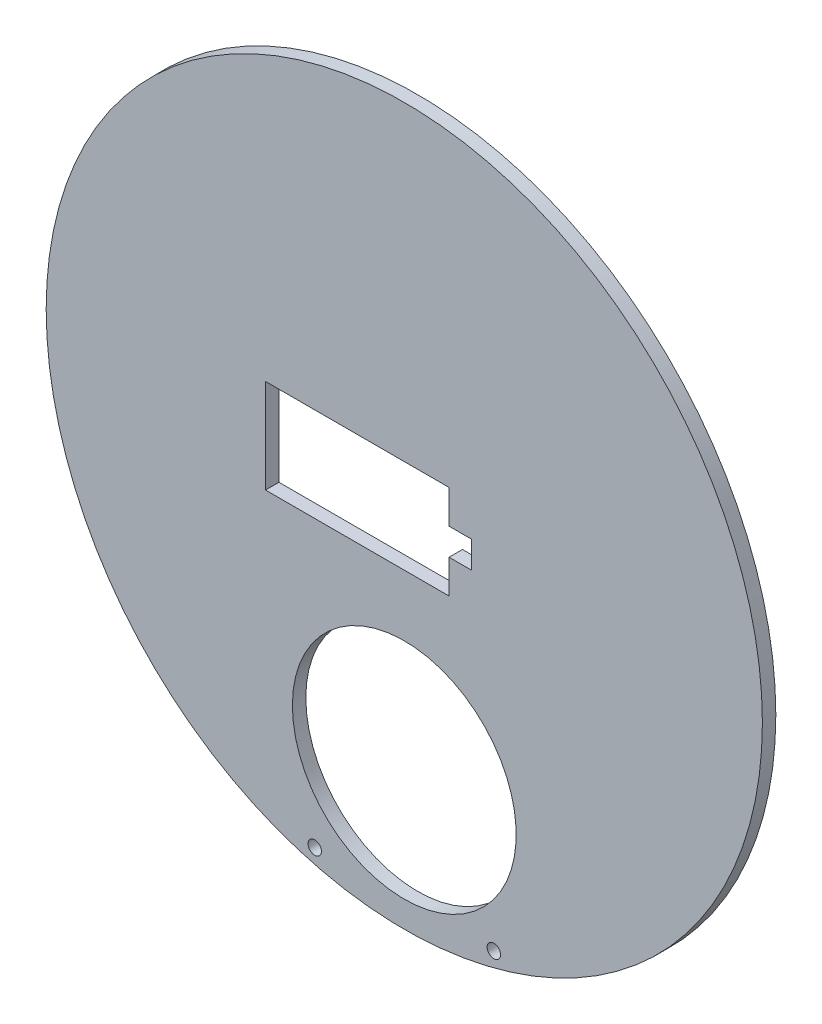
SolidWorks part; units mm, degrees
ref_plane "Plan de face" through (0, 0, 0) normal (0, 0, 1) x (1, 0, 0)
ref_plane "Plan de dessus" through (0, 0, 0) normal (0, 1, 0) x (1, 0, 0)
ref_plane "Plan de droite" through (0, 0, 0) normal (1, 0, 0) x (0, 0, -1)
sketch "Esquisse1" plane through (0, 0, 0) normal (0, 0, 1) x (1, 0, 0)
  circle A0 centre (-11.1979, 8.2445) radius 80
  dimension "D1" = 160
extrude "Boss.-Extru.1" add sketch "Esquisse1" along normal blind 3
sketch "Esquisse2" plane through (0, 0, 0) normal (0, 0, -1) x (-1, 0, 0)
  line L0 (11.1979, 88.2445) -> (11.1979, -71.7555) construction
  line L1 (91.1979, 8.2445) -> (-68.8021, 8.2445) construction
  line L2 (1.1979, 5.2445) -> (1.1979, -2.2555)
  line L3 (1.1979, 18.7445) -> (42.1979, 18.7445)
  line L4 (1.1979, 18.7445) -> (1.1979, 11.2445)
  line L5 (1.1979, -2.2555) -> (42.1979, -2.2555)
  line L6 (42.1979, 18.7445) -> (42.1979, -2.2555)
  line L7 (-3.8021, 11.2445) -> (1.1979, 11.2445)
  line L8 (-3.8021, 11.2445) -> (-3.8021, 5.2445)
  line L9 (-3.8021, 5.2445) -> (1.1979, 5.2445)
  circle A0 centre (11.1979, 8.2445) radius 80 construction
  circle A1 centre (11.1979, 8.2445) radius 1
  dimension "D1" = 2
  dimension "D4" = 10.5
  dimension "D2" = 41
  dimension "D3" = 21
  dimension "D5" = 10
  dimension "D6" = 5
  dimension "D7" = 6
  dimension "D8" = 7.5
extrude "Enlèv. mat.-Extru.1" cut sketch "Esquisse2" against normal blind 3 contours L8 L9 L2 L5 L6 L3 L4 L7 A1 | A1
sketch "Esquisse3" plane through (0, 0, 0) normal (0, 0, -1) x (-1, 0, 0)
  line L0 (11.1979, 88.2445) -> (11.1979, -71.7555) construction
  line L1 (-18.8021, -65.9175) -> (-18.8021, -40.9175)
  line L3 (41.1979, -40.9175) -> (41.1979, -65.9175)
  circle A0 centre (11.1979, 8.2445) radius 80 construction
  arc A1 (-18.8021, -40.9175) -> (41.1979, -40.9175) centre (11.1979, -40.9175) cw
  arc A2 (-18.8021, -65.9175) -> (41.1979, -65.9175) centre (11.1979, 8.2445) ccw
  circle A3 centre (11.1979, -40.9175) radius 25
  circle A4 centre (-8.8021, -65.9199) radius 1.5
  circle A5 centre (31.1979, -65.9175) radius 1.5
  dimension "D5" = 30
  dimension "D4" = 3
  dimension "D6" = 3
  dimension "D8" = 40
  dimension "D10" = 25.0024
  dimension "D11" = 25
  dimension "D2" = 50
  dimension "D1" = 60
  dimension "D3" = 25
  dimension "D9" = 20
extrude "Enlèv. mat.-Extru.10" cut sketch "Esquisse3" against normal blind 3 contours L0 A3 | A3 L0 | A4 | A5
